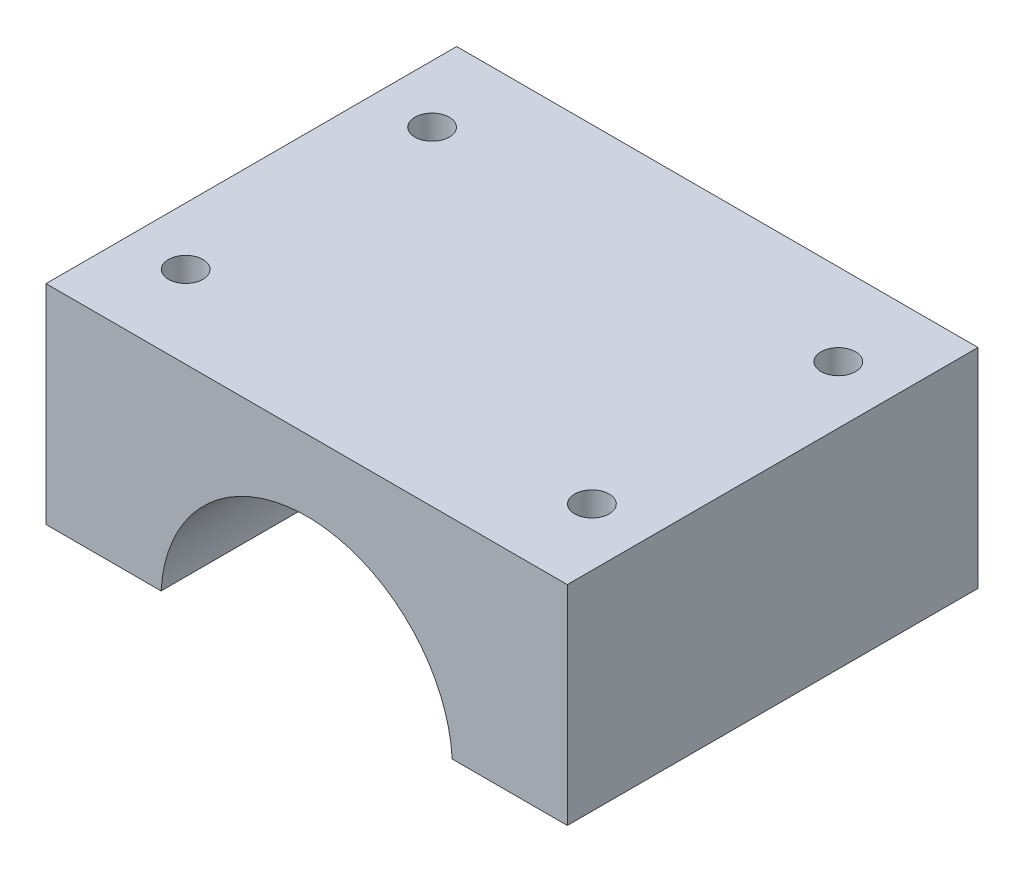
SolidWorks part; units mm, degrees
ref_plane "Front" through (0, 0, 0) normal (0, 0, 1) x (1, 0, 0)
ref_plane "Top" through (0, 0, 0) normal (0, 1, 0) x (1, 0, 0)
ref_plane "Right" through (0, 0, 0) normal (1, 0, 0) x (0, 0, -1)
sketch "Sketch1" plane through (0, 0, 0) normal (0, 0, 1) x (1, 0, 0)
  line L0 (-31.75, 0) -> (31.75, 0) construction
  line L1 (-31.7342, 1) -> (-17.7218, 1)
  line L2 (-31.75, 1) -> (31.75, 1) construction
  line L3 (17.7218, 1) -> (31.7342, 1)
  arc A0 (31.7342, 1) -> (-31.7342, 1) centre (0, 0) ccw
  arc A1 (17.7218, 1) -> (-17.7218, 1) centre (0, 0) ccw
  dimension "D1" = 35.5
  dimension "D2" = 63.5
  dimension "D3" = 1
extrude "Boss-Extrude1" add sketch "Sketch1" along normal blind 50
sketch "Sketch4" plane through (0, 0, 50) normal (0, 0, 1) x (1, 0, 0)
  line L0 (0, 31.75) -> (-31.7342, 31.75)
  line L1 (-31.7342, 31.75) -> (-31.7342, 1)
  line L2 (0, 31.75) -> (31.7342, 31.75)
  line L3 (31.7342, 31.75) -> (31.7342, 1)
  arc A0 (31.7342, 1) -> (-31.7342, 1) centre (0, 0) ccw construction
  arc A1 (31.7342, 1) -> (-31.7342, 1) centre (0, 0) ccw
  arc M1 (31.7342, 1) -> (-31.7342, 1) centre (0, 0) ccw
extrude "Boss-Extrude2" add sketch "Sketch4" against normal up to surface (50 mm away) contours L3 L2 M1 | L0 L1 M1 up to face at (0, 12.875, 0)
sketch "Sketch2" plane through (0, 1, 0) normal (0, -1, 0) x (-1, 0, 0)
  line L0 (24.728, -50) -> (24.728, 0) construction
  line L1 (31.7342, -50) -> (17.7218, -50) construction
  line L2 (31.7342, 0) -> (17.7218, 0) construction
  line L3 (-24.728, -50) -> (-24.728, 0) construction
  line L4 (-17.7218, -50) -> (-31.7342, -50) construction
  line L5 (-17.7218, 0) -> (-31.7342, 0) construction
  line L6 (0, -50) -> (0, 0) construction
  line L7 (-17.7218, -50) -> (17.7218, -50) construction
  circle A0 centre (24.728, -40) radius 1
  circle A1 centre (24.728, -10) radius 1
  circle A2 centre (-24.728, -10) radius 1
  circle A3 centre (-24.728, -40) radius 1
  dimension "D1" = 10
  dimension "D2" = 10
  dimension "D3" = 2
hole_wizard "Tap Drill for M5x0.8 Tap1" positions "3DSketch1" profile "Sketch3" hole size "M5x0.8" standard "ANSI Metric" end condition up to next
sketch3d "3DSketch1"
  point P0 (-24.728, 1, 40)
  point P3 (-24.728, 1, 10)
  point P6 (24.728, 1, 40)
  point P9 (24.728, 1, 10)
sketch "Sketch3" plane through (-24.728, 1, 40) normal (1, 0, 0) x (0, 0, -1)
  line L0 (0, 0) -> (0, 30.75)
  line L1 (0, 30.75) -> (2.1, 30.75)
  line L2 (2.1, 30.75) -> (2.1, 0)
  line L5 (2.1, 0) -> (0, 0)
  line L11 (0, -6.35) -> (0, 107.95) construction
  dimension "Thru Hole Dia." = 4.2
  dimension "Thru Hole Depth" = 30.75
sketch "Sketch5" plane through (0, 0, 50) normal (0, 0, 1) x (1, 0, 0)
  line L0 (31.7342, 31.75) -> (31.7342, 1) construction
  line L1 (-31.7342, 31.75) -> (31.7342, 31.75)
  line L2 (-31.7342, 31.75) -> (-31.7342, 26.4)
  line L3 (-31.7342, 26.4) -> (31.7342, 26.4)
  line L4 (31.7342, 31.75) -> (31.7342, 26.4)
  line L5 (-31.7342, 31.75) -> (31.7342, 26.4) construction
  line L6 (-31.7342, 26.4) -> (31.7342, 31.75) construction
  line L7 (17.7218, 1) -> (31.7342, 1) construction
  point P4 (0, 29.075)
  dimension "D1" = 25.4
extrude "Cut-Extrude1" cut sketch "Sketch5" against normal up to next
